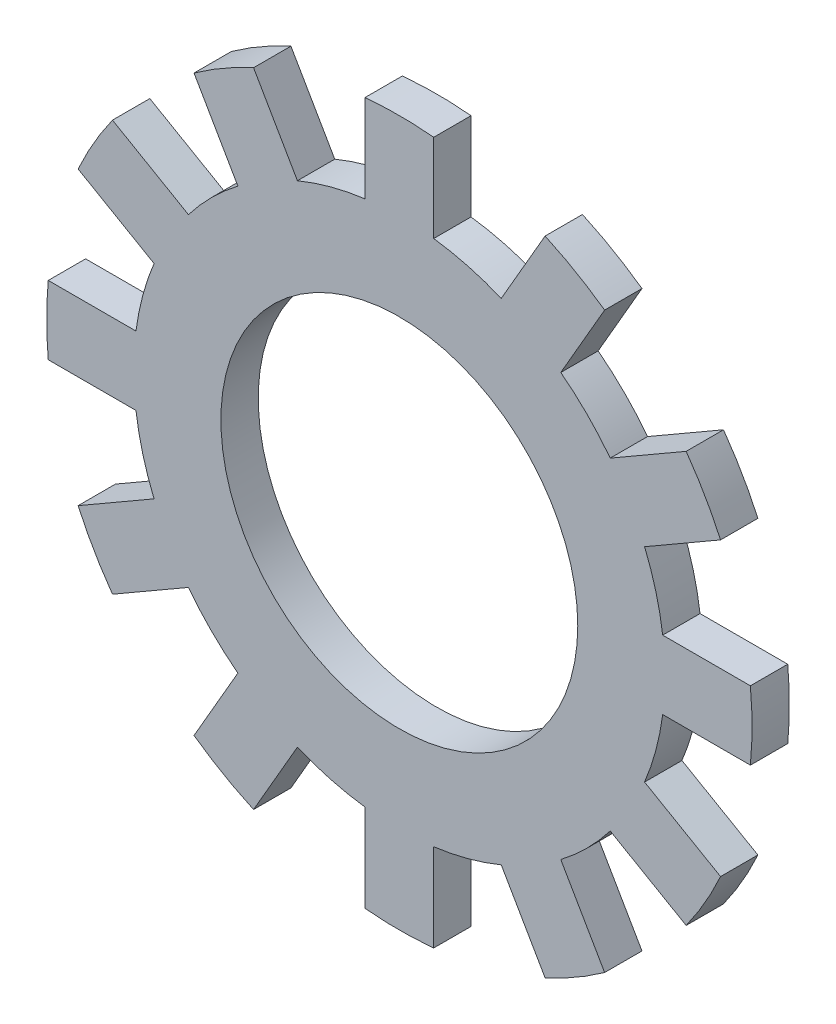
SolidWorks part; units mm, degrees
ref_plane "Front Plane" through (0, 0, 0) normal (0, 0, 1) x (1, 0, 0)
ref_plane "Top Plane" through (0, 0, 0) normal (0, 1, 0) x (1, 0, 0)
ref_plane "Right Plane" through (0, 0, 0) normal (1, 0, 0) x (0, 0, -1)
sketch "Sketch1" plane through (0, 0, 0) normal (0, 0, 1) x (1, 0, 0)
  circle A0 centre (0, 0) radius 4.25 construction
  circle A1 centre (0, 0) radius 2.15
  circle A2 centre (0, 0) radius 3.2
  dimension "D1" = 6.4
  dimension "A" = 4.3
  dimension "B" = 8.5
extrude "Extrude1" add sketch "Sketch1" along normal blind 0.45
sketch "Sketch2" plane through (0, 0, 0) normal (0, 0, 1) x (1, 0, 0)
  line L0 (0, 0) -> (0, 4.25) construction
  line L1 (0, 0) -> (1.1, 4.1052) construction
  line L2 (0, 0) -> (-1.1, 4.1052) construction
  line L3 (-0.8282, 3.091) -> (0, 3.091) construction
  line L4 (-0.4141, 4.2298) -> (-0.4141, 3.1731)
  line L5 (0.4141, 4.2298) -> (0.4141, 3.1731)
  line L6 (-0.4141, 3.1731) -> (0.4141, 3.1731)
  circle A0 centre (0, 0) radius 3.2 construction
  circle A1 centre (0, 0) radius 3.2 construction
  circle A2 centre (0, 0) radius 4.25 construction
  arc A3 (0.4141, 4.2298) -> (-0.4141, 4.2298) centre (0, 0) ccw
  dimension "D2" = 15
  dimension "D3" = 15
extrude "Extrude2" add sketch "Sketch2" along normal up to surface (0.45 mm away) up to face at (3.2, 0, 0.45)
pattern_circular "CirPattern1" count 12 over 360 about axis through (0, 0, 0) along (0, 0, 1) of "Extrude2"
sketch "Sketch3" plane through (0, 0, 0) normal (0, 0, 1) x (1, 0, 0)
  line L0 (-0.4944, 4.2211) -> (-0.4944, 3.1616)
  line L1 (0.4944, 4.2211) -> (0.4944, 3.1616)
  line L2 (0, 0) -> (0, 4.25) construction
  line L3 (0, 0) -> (1.3133, 4.042) construction
  line L4 (0, 0) -> (-1.3133, 4.042) construction
  line L5 (-0.9889, 3.0434) -> (0, 3.0434) construction
  line L6 (-0.4944, 3.1616) -> (0.4944, 3.1616)
  circle A0 centre (0, 0) radius 4.25 construction
  circle A1 centre (0, 0) radius 3.2 construction
  circle A2 centre (0, 0) radius 3.2 construction
  arc A3 (0.4944, 4.2211) -> (-0.4944, 4.2211) centre (0, 0) ccw
  dimension "D2" = 18
  dimension "D3" = 18
extrude "Extrude3" [suppressed] add sketch "Sketch3" along normal up to surface (0.25 mm away)
pattern_circular "CirPattern2" [suppressed] count 10 over 360
equation "\"D1@Sketch1\" =  ( \"B@Sketch1\" + \"A@Sketch1\" )  / 2"
